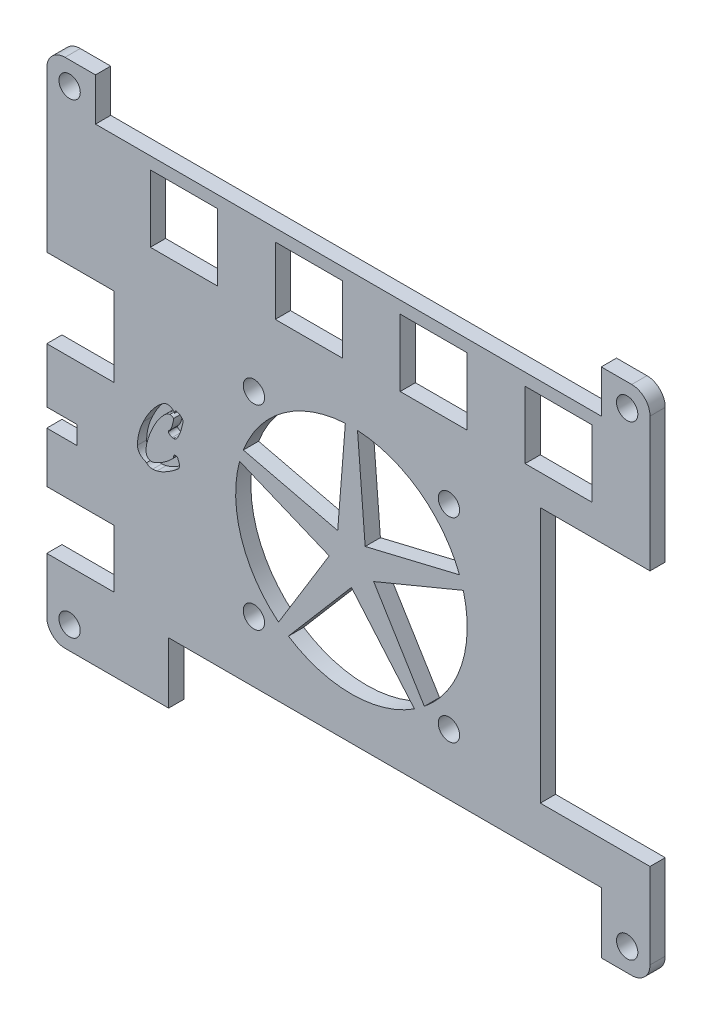
SolidWorks part; units mm, degrees
ref_plane "前基準面" through (0, 0, 0) normal (0, 0, 1) x (1, 0, 0)
ref_plane "上基準面" through (0, 0, 0) normal (0, 1, 0) x (1, 0, 0)
ref_plane "右基準面" through (0, 0, 0) normal (1, 0, 0) x (0, 0, -1)
sketch "草圖1" plane through (0, 0, 0) normal (0, 0, 1) x (1, 0, 0)
  line L0 (0, 42) -> (0, -42) construction
  line L1 (-46.5, 42) -> (46.5, 42)
  line L2 (-49.5, 39) -> (-49.5, -39)
  line L3 (-46.5, -42) -> (46.5, -42)
  line L4 (49.5, 39) -> (49.5, -39)
  line L5 (-49.5, 0) -> (49.5, 0) construction
  circle A0 centre (-45.75, 38.25) radius 1.75
  circle A1 centre (45.75, 38.25) radius 1.75
  circle A2 centre (45.75, -38.25) radius 1.75
  circle A3 centre (-45.75, -38.25) radius 1.75
  arc A4 (-46.5, -42) -> (-49.5, -39) centre (-46.5, -39) cw
  arc A5 (46.5, -42) -> (49.5, -39) centre (46.5, -39) ccw
  arc A6 (49.5, 39) -> (46.5, 42) centre (46.5, 39) ccw
  arc A7 (-46.5, 42) -> (-49.5, 39) centre (-46.5, 39) ccw
  point P4 (-49.5, 0)
  point P7 (0, -42)
  point P22 (-49.5, -42)
  point P27 (49.5, 42)
  point P30 (-49.5, 42)
  dimension "D3" = 3.5
  dimension "D6" = 3
  dimension "D1" = 99
  dimension "D2" = 84
  dimension "D4" = 3.75
  dimension "D5" = 3.75
extrude "填料-伸長1" add sketch "草圖1" along normal blind 2.5
sketch "草圖2" plane through (0, 0, 2.5) normal (0, 0, 1) x (1, 0, 0)
  line L0 (-49.5, -30) -> (-38.5, -30)
  line L1 (-49.5, 39) -> (-49.5, -39) construction
  line L2 (-38.5, -30) -> (-38.5, -20.5)
  line L3 (-38.5, -20.5) -> (-49.5, -20.5)
  line L4 (49.5, -39) -> (49.5, 39) construction
  line L5 (-49.5, -9.2) -> (-44.5, -9.2)
  line L6 (-49.5, -9.2) -> (-49.5, -12.2)
  line L7 (-49.5, -12.2) -> (-44.5, -12.2)
  line L8 (-44.5, -9.2) -> (-44.5, -12.2)
  line L9 (-49.5, 12.8) -> (-38.5, 12.8)
  line L10 (-49.5, 12.8) -> (-49.5, -0.2)
  line L11 (-49.5, -0.2) -> (-38.5, -0.2)
  line L12 (-38.5, 12.8) -> (-38.5, -0.2)
  line L13 (49.5, 17) -> (31.5, 17)
  line L14 (49.5, 17) -> (49.5, -25)
  line L15 (49.5, -25) -> (31.5, -25)
  line L16 (31.5, 17) -> (31.5, -25)
  line L17 (-46.5, -42) -> (46.5, -42) construction
  line L18 (-32.5, 33) -> (-21.5, 33)
  line L19 (-32.5, 33) -> (-32.5, 22)
  line L20 (-32.5, 22) -> (-21.5, 22)
  line L21 (-21.5, 33) -> (-21.5, 22)
  line L22 (-12, 33) -> (-1, 33)
  line L23 (-12, 33) -> (-12, 22)
  line L24 (-12, 22) -> (-1, 22)
  line L25 (-1, 33) -> (-1, 22)
  line L26 (8.5, 33) -> (19.5, 33)
  line L27 (8.5, 33) -> (8.5, 22)
  line L28 (8.5, 22) -> (19.5, 22)
  line L29 (19.5, 33) -> (19.5, 22)
  line L30 (29, 33) -> (40, 33)
  line L31 (29, 33) -> (29, 22)
  line L32 (29, 22) -> (40, 22)
  line L33 (40, 33) -> (40, 22)
  line L34 (46.5, 42) -> (-46.5, 42) construction
  line L35 (-41.5, 42) -> (41.5, 42)
  line L36 (-41.5, 42) -> (-41.5, 35)
  line L37 (-41.5, 35) -> (41.5, 35)
  line L38 (41.5, 42) -> (41.5, 35)
  line M33 (49.5, -39) -> (49.5, 39)
  line M35 (46.5, 42) -> (-46.5, 42)
  line M37 (-49.5, 39) -> (-49.5, -39)
  dimension "D1" = 12
  dimension "D2" = 9.5
  dimension "D3" = 8.3
  dimension "D4" = 9
  dimension "D5" = 13
  dimension "D6" = 11
  dimension "D7" = 5
  dimension "D8" = 11
  dimension "D9" = 17
  dimension "D10" = 42
  dimension "D11" = 18
  dimension "D12" = 5
  dimension "D13" = 11
  dimension "D14" = 11
  dimension "D15" = 11
  dimension "D16" = 11
  dimension "D17" = 11
  dimension "D18" = 9.5
  dimension "D19" = 9.5
  dimension "D20" = 9.5
  dimension "D21" = 17
  dimension "D22" = 8
  dimension "D23" = 8
  dimension "D24" = 7
  dimension "D25" = 3
  dimension "D26" = 9.5
extrude "除料-伸長1" cut sketch "草圖2" against normal blind 3 contours L12 L9 L11 M37 | L2 L3 L0 M37 | L8 L5 L7 M37 | L13 L16 L15 M33 | L33 L30 L31 L32 | L29 L26 L27 L28 | L25 L22 L23 L24 | L21 L18 L19 L20 | L38 L36 L37 M35
sketch "草圖3" plane through (0, 0, 2.5) normal (0, 0, 1) x (1, 0, 0)
  line L0 (-46.5, -42) -> (46.5, -42) construction
  line L1 (-15.5, 10) -> (16.5, 10) construction
  line L2 (-15.5, 10) -> (-15.5, -22) construction
  line L3 (-15.5, -22) -> (16.5, -22) construction
  line L4 (16.5, 10) -> (16.5, -22) construction
  line L5 (31.5, 17) -> (31.5, -25) construction
  line L6 (-38.5, -30) -> (-38.5, -20.5) construction
  circle A0 centre (-15.5, 10) radius 1.75
  circle A1 centre (16.5, 10) radius 1.75
  circle A2 centre (16.5, -22) radius 1.75
  circle A3 centre (-15.5, -22) radius 1.75
  dimension "D6" = 3.5
  dimension "D7" = 3.5
  dimension "D8" = 3.5
  dimension "D9" = 3.5
  dimension "D1" = 32
  dimension "D2" = 32
  dimension "D3" = 20
  dimension "D4" = 15
  dimension "D5" = 23
extrude "除料-伸長2" cut sketch "草圖3" against normal through all
sketch "草圖4" plane through (0, 0, 2.5) normal (0, 0, 1) x (1, 0, 0)
  line L0 (0.5, 10) -> (0.5, -22) construction
  line L1 (-15.5, 10) -> (16.5, 10) construction
  line L2 (-15.5, 10) -> (-15.5, -22) construction
  line L3 (-15.5, -22) -> (16.5, -22) construction
  line L4 (16.5, 10) -> (16.5, -22) construction
  line L5 (-15.5, -6) -> (16.5, -6) construction
  line L6 (-19.5, 14) -> (20.5, 14) construction
  line L7 (20.5, 14) -> (20.5, -26) construction
  line L8 (-19.5, -26) -> (20.5, -26) construction
  line L9 (-19.5, 14) -> (-19.5, -26) construction
  line L10 (-0.5, 12.9737) -> (-1.7547, -2.8967)
  line L11 (1.5, 12.9737) -> (2.7547, -2.8967)
  line L12 (18.236, 0.8142) -> (2.7547, -2.8967)
  line L13 (18.854, -1.0879) -> (4.1481, -7.1853)
  line L14 (12.4615, -20.7622) -> (4.1481, -7.1853)
  line L15 (10.8434, -21.9378) -> (0.5, -9.8359)
  line L16 (-9.8434, -21.9378) -> (0.5, -9.8359)
  line L17 (-11.4615, -20.7622) -> (-3.1481, -7.1853)
  line L18 (-17.854, -1.0879) -> (-3.1481, -7.1853)
  line L19 (-17.236, 0.8142) -> (-1.7547, -2.8967)
  arc A0 (-9.8434, -21.9378) -> (10.8434, -21.9378) centre (0.5, -6) ccw
  arc A1 (-17.854, -1.0879) -> (-11.4615, -20.7622) centre (0.5, -6) ccw
  arc A2 (-0.5, 12.9737) -> (-17.236, 0.8142) centre (0.5, -6) ccw
  arc A3 (18.236, 0.8142) -> (1.5, 12.9737) centre (0.5, -6) ccw
  arc A4 (12.4615, -20.7622) -> (18.854, -1.0879) centre (0.5, -6) ccw
  point P39 (0.5, -6)
  dimension "D3" = 38
  dimension "D7" = 38
  dimension "D1" = 32
  dimension "D2" = 32
  dimension "D5" = 40
  dimension "D6" = 40
  dimension "D9" = 1
  dimension "D4" = 4
  dimension "D10" = 5
extrude "除料-伸長3" cut sketch "草圖4" against normal through all
sketch "草圖6" plane through (0, 0, 2.5) normal (0, 0, 1) x (1, 0, 0)
  line L0 (-46.5, -42) -> (46.5, -42) construction
  line L1 (-29.5, -32) -> (41.5, -32)
  line L2 (-29.5, -32) -> (-29.5, -42)
  line L3 (-29.5, -42) -> (41.5, -42)
  line L4 (41.5, -32) -> (41.5, -42)
  line L5 (49.5, -39) -> (49.5, -25) construction
  line L6 (-49.5, -30) -> (-49.5, -39) construction
  dimension "D1" = 8
  dimension "D2" = 20
  dimension "D3" = 10
extrude "除料-伸長4" cut sketch "草圖6" against normal through all both and the other way through all
sketch "草圖7" plane through (0, 0, 2.5) normal (0, 0, 1) x (1, 0, 0)
  line L0 (-44.5, -9.2) -> (-18.2286, -9.2) construction
  line L1 (-44.5, -9.2) -> (-44.5, -12.2) construction
  line L2 (-49.5, -9.2) -> (-44.5, -9.2) construction
  arc A0 (-17.854, -1.0879) -> (-11.4615, -20.7622) centre (0.5, -6) ccw construction
  text T0 "C" font "Pristina" height in points 36
extrude "除料-伸長5" cut sketch "草圖7" against normal blind 1.5
